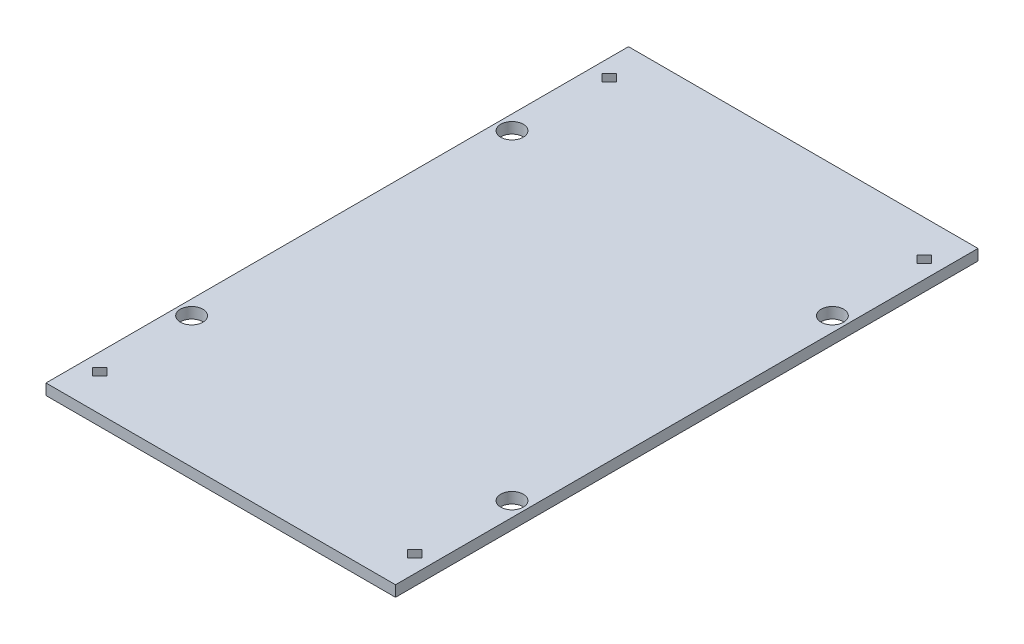
SolidWorks part; units mm, degrees
ref_plane "前视基准面" through (0, 0, 0) normal (0, 0, 1) x (1, 0, 0)
ref_plane "上视基准面" through (0, 0, 0) normal (0, 1, 0) x (1, 0, 0)
ref_plane "右视基准面" through (0, 0, 0) normal (1, 0, 0) x (0, 0, -1)
other "Configuration Table"
sketch "草图1" plane through (0, 0, 0) normal (0, 1, 0) x (1, 0, 0)
  line L0 (-37.1437, 0) -> (40.4211, 0) construction
  line L1 (-24, 40) -> (24, 40)
  line L2 (-24, 40) -> (-24, -40)
  line L3 (-24, -40) -> (24, -40)
  line L4 (24, 40) -> (24, -40)
  line L5 (-24, 40) -> (24, -40) construction
  line L6 (-24, -40) -> (24, 40) construction
  line L7 (0, 54.8279) -> (0, -51.0043) construction
  line L8 (22.62, 35) -> (21.62, 34)
  line L9 (-21.62, 34) -> (-20.62, 35)
  line L10 (-20.62, 35) -> (-21.62, 36)
  line L11 (-21.62, 36) -> (-22.62, 35)
  line L12 (-22.62, 35) -> (-21.62, 34)
  line L13 (21.62, 36) -> (22.62, 35)
  line L14 (20.62, 35) -> (21.62, 36)
  line L15 (21.62, 34) -> (20.62, 35)
  line L16 (21.62, -36) -> (22.62, -35)
  line L17 (20.62, -35) -> (21.62, -36)
  line L18 (21.62, -34) -> (20.62, -35)
  line L19 (22.62, -35) -> (21.62, -34)
  line L20 (-22.62, -35) -> (-21.62, -34)
  line L21 (-21.62, -36) -> (-22.62, -35)
  line L22 (-20.62, -35) -> (-21.62, -36)
  line L23 (-21.62, -34) -> (-20.62, -35)
  circle A0 centre (-21.62, 35) radius 0.7071 construction
  circle A1 centre (-22, 22) radius 1.55
  circle A2 centre (22, 22) radius 1.55
  circle A3 centre (22, -22) radius 1.55
  circle A4 centre (-22, -22) radius 1.55
  point P0 (0, 0)
  dimension "D8" = 3.1
  dimension "D1" = 80
  dimension "D2" = 48
  dimension "D3" = 35
  dimension "D4" = 21.62
  dimension "D5" = 2
  dimension "D6" = 22
  dimension "D7" = 22
extrude "凸台-拉伸1" add sketch "草图1" along normal blind 1.5
